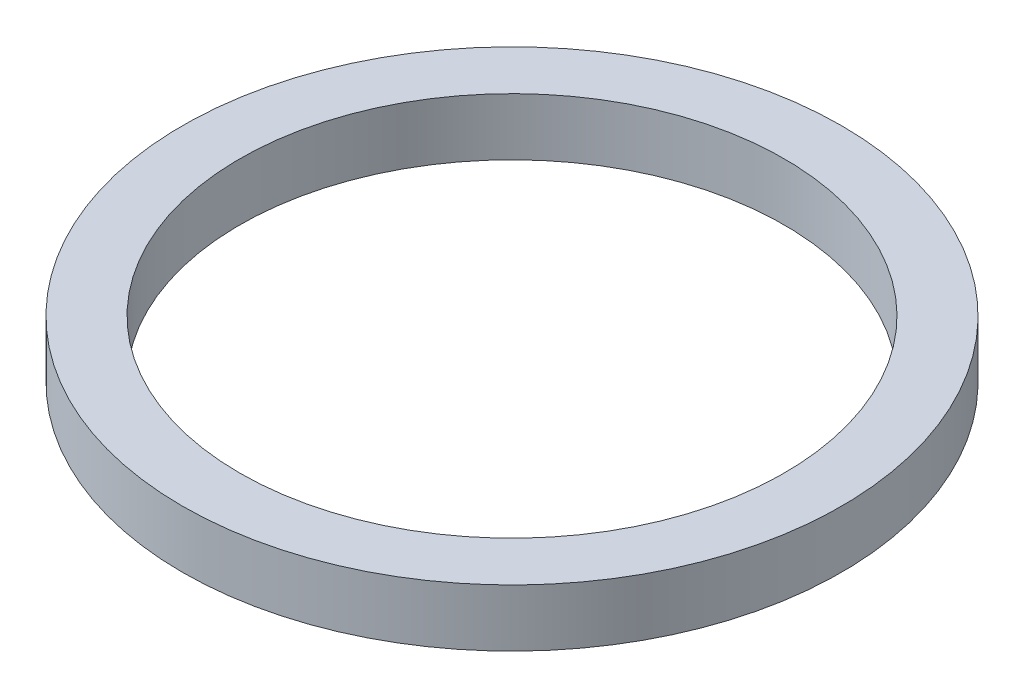
SolidWorks part; units mm, degrees
ref_plane "Front Plane" through (0, 0, 0) normal (0, 0, 1) x (1, 0, 0)
ref_plane "Top Plane" through (0, 0, 0) normal (0, 1, 0) x (1, 0, 0)
ref_plane "Right Plane" through (0, 0, 0) normal (1, 0, 0) x (0, 0, -1)
sketch "Sketch1" plane through (0, 0, 0) normal (0, 1, 0) x (1, 0, 0)
  circle A0 centre (0, 0) radius 5.75
  circle A1 centre (0, 0) radius 4.75
  dimension "D1" = 11.5
  dimension "D2" = 1
extrude "Boss-Extrude1" add sketch "Sketch1" along normal blind 1
